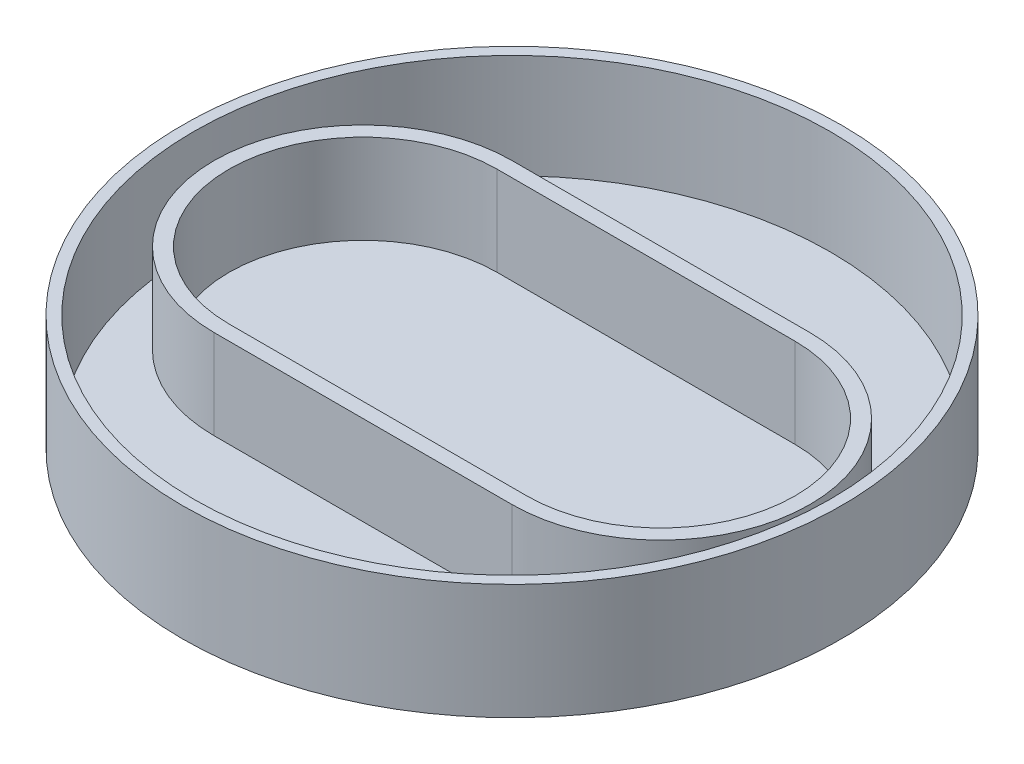
SolidWorks part; units mm, degrees
material "Plexiglas"
ref_plane "Front" through (0, 0, 0) normal (0, 0, 1) x (1, 0, 0)
ref_plane "Top" through (0, 0, 0) normal (0, 1, 0) x (1, 0, 0)
ref_plane "Right" through (0, 0, 0) normal (1, 0, 0) x (0, 0, -1)
sketch "Esquisse1" plane through (0, 0, 0) normal (0, 0, 1) x (1, 0, 0)
  line L0 (0, 0) -> (0, 15.5) construction
  line L1 (0, 0) -> (44.25, 0)
  line L2 (44.25, 15.5) -> (44.25, 0)
  line L3 (44.25, 15.5) -> (42.75, 15.5)
  line L4 (42.75, 15.5) -> (42.75, 1.5)
  line L5 (42.75, 1.5) -> (0, 1.5)
  line L6 (0, 0) -> (0, 1.5)
  dimension "D1" = 15.5
  dimension "D2" = 88.5
  dimension "D3" = 1.5
  dimension "D4" = 1.5
revolve "Révolution1" add sketch "Esquisse1" angle 360 about L0
sketch "Esquisse4" plane through (0, 1.5, 0) normal (0, 1, 0) x (1, 0, 0)
  line L0 (-20, -20) -> (20, -20)
  line L1 (20, 20) -> (-20, 20)
  line L2 (20, 18) -> (20, 20) construction
  line L3 (20, -18) -> (-20, -18)
  line L4 (-20, -18) -> (-20, -20) construction
  line L5 (-20, 18) -> (20, 18)
  arc A0 (20, -20) -> (20, 20) centre (20, 0) ccw
  arc A1 (-20, 20) -> (-20, -20) centre (-20, 0) ccw
  arc A2 (20, 18) -> (20, -18) centre (20, 0) cw
  arc A3 (-20, -18) -> (-20, 18) centre (-20, 0) cw
  point P11 (0, 0)
  point P17 (0, 0)
  point P18 (0, 0)
  dimension "D1" = 20
  dimension "D2" = 20
  dimension "D3" = 40
  dimension "D4" = 20
  dimension "D6" = 2
  dimension "D5" = 2
  dimension "D7" = 2
extrude "Boss.-Extru.3" add sketch "Esquisse4" along normal blind 12 contours L1 A1 L0 A0 L3 A3 L5 A2
